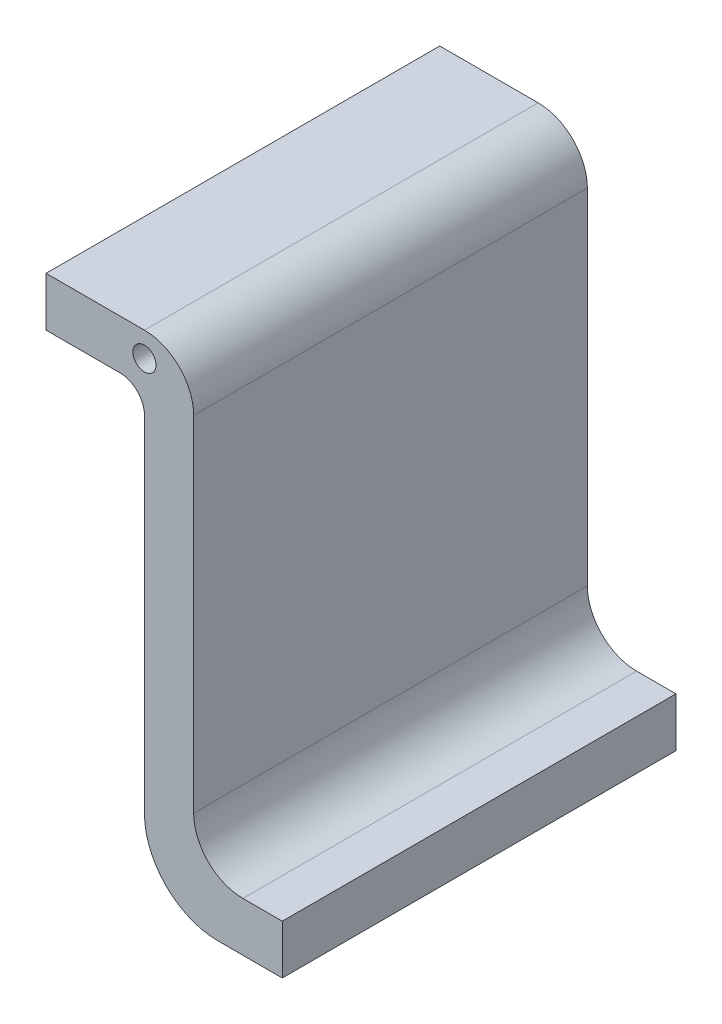
SolidWorks part; units mm, degrees
material "PLA"
ref_plane "Alzado" through (0, 0, 0) normal (0, 0, 1) x (1, 0, 0)
ref_plane "Planta" through (0, 0, 0) normal (0, 1, 0) x (1, 0, 0)
ref_plane "Vista lateral" through (0, 0, 0) normal (1, 0, 0) x (0, 0, -1)
sketch "Croquis1" plane through (0, 0, 0) normal (0, 0, 1) x (1, 0, 0)
  line L0 (0, 0) -> (20, 0)
  line L1 (30, -10) -> (30, -80)
  line L2 (40, -90) -> (48, -90)
  line L5 (20, -100) -> (20, -10)
  line L6 (20, -10) -> (0, -10)
  line L7 (0, -10) -> (0, 0)
  line L10 (48, -100) -> (20, -100)
  line L11 (48, -100) -> (48, -90)
  arc A0 (20, 0) -> (30, -10) centre (20, -10) cw
  arc A1 (30, -80) -> (40, -90) centre (40, -80) ccw
  point P11 (30, 0)
  point P14 (30, -90)
  dimension "D4" = 10
  dimension "D1" = 30
  dimension "D2" = 90
  dimension "D3" = 10
  dimension "D5" = 18
  dimension "D6" = 10
  dimension "D7" = 10
extrude "Saliente-Extruir3" add sketch "Croquis1" against normal blind 80
sketch "Croquis2" plane through (0, 0, 0) normal (0, 0, 1) x (1, 0, 0)
  line L0 (20, 0) -> (0, 0) construction
  line L1 (0, 0) -> (0, -10) construction
  circle A0 centre (20, -5) radius 2.35
  dimension "D1" = 4.7
  dimension "D2" = 5
  dimension "D3" = 20
extrude "Cortar-Extruir1" cut sketch "Croquis2" against normal blind 5
sketch "Croquis3" plane through (0, 0, -80) normal (0, 0, -1) x (-1, 0, 0)
  circle A0 centre (-20, -5) radius 2.35
  dimension "D1" = 4.7
extrude "Cortar-Extruir2" cut sketch "Croquis3" against normal blind 5
fillet "Redondeo1" radius 15 1 edges at (20, -100, -40)
fillet "Redondeo3" radius 5 1 edges at (20, -10, -40)
